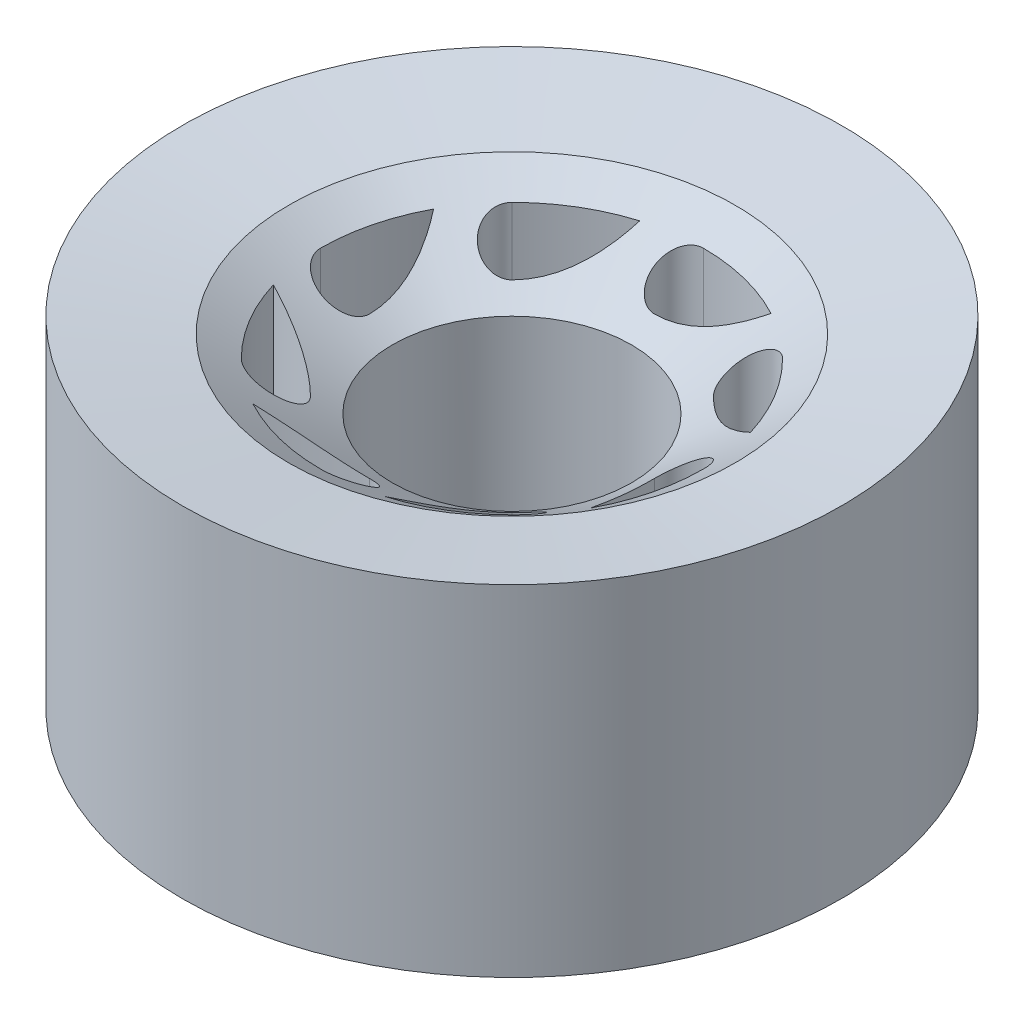
SolidWorks part; units mm, degrees
ref_plane "前视基准面" through (0, 0, 0) normal (0, 0, 1) x (1, 0, 0)
ref_plane "上视基准面" through (0, 0, 0) normal (0, 1, 0) x (1, 0, 0)
ref_plane "右视基准面" through (0, 0, 0) normal (1, 0, 0) x (0, 0, -1)
sketch "草图3" plane through (0, 0, 0) normal (1, 0, 0) x (0, 0, -1)
  line L0 (0, 291.9449) -> (0, 187.2391) construction
  line L1 (0, 211.2391) -> (11.25, 211.2391)
  line L2 (11.25, 211.2391) -> (21, 217.7391)
  line L3 (21, 217.7391) -> (31, 219.2391)
  line L4 (31, 219.2391) -> (31, 187.2391)
  line L5 (0, 187.2391) -> (31, 187.2391)
  line L6 (0, 187.2391) -> (0, 211.2391)
  dimension "D1" = 32
  dimension "D2" = 10
  dimension "D3" = 1.5
  dimension "D4" = 6.5
  dimension "D5" = 11.25
  dimension "D6" = 31
revolve "旋转1" add sketch "草图3" angle 360 about L0
sketch "草图5" plane through (0, 187.2391, 0) normal (0, -1, 0) x (1, 0, 0)
  circle A0 centre (0, 0) radius 4
  dimension "D1" = 8
extrude "切除-拉伸1" cut sketch "草图5" against normal through all contours A0
sketch "草图6" plane through (0, 187.2391, 0) normal (0, -1, 0) x (1, 0, 0)
  line L0 (0, 25.1257) -> (0, -39.6874) construction
  line L1 (-35.1563, 0) -> (34.447, 0) construction
  arc A0 (0, 18) -> (0, 13.4) centre (0, 15.7) cw
  arc A2 (-18, 0) -> (-15.8675, -8.4983) centre (0, 0) ccw
  arc A3 (0, 13.4) -> (-8.4983, 15.8675) centre (0, 29.2683) cw
  arc A4 (0, 18) -> (-8.4983, 15.8675) centre (0, 0) ccw
  arc A5 (12.7279, 12.7279) -> (9.4752, 9.4752) centre (11.1016, 11.1016) cw
  arc A6 (9.4752, 9.4752) -> (5.2108, 17.2293) centre (20.6958, 20.6958) cw
  arc A7 (12.7279, 12.7279) -> (5.2108, 17.2293) centre (0, 0) ccw
  arc A8 (18, 0) -> (13.4, 0) centre (15.7, 0) cw
  arc A9 (13.4, 0) -> (15.8675, 8.4983) centre (29.2683, 0) cw
  arc A10 (18, 0) -> (15.8675, 8.4983) centre (0, 0) ccw
  arc A11 (12.7279, -12.7279) -> (9.4752, -9.4752) centre (11.1016, -11.1016) cw
  arc A12 (9.4752, -9.4752) -> (17.2293, -5.2108) centre (20.6958, -20.6958) cw
  arc A13 (12.7279, -12.7279) -> (17.2293, -5.2108) centre (0, 0) ccw
  arc A14 (0, -18) -> (0, -13.4) centre (0, -15.7) cw
  arc A15 (0, -13.4) -> (8.4983, -15.8675) centre (0, -29.2683) cw
  arc A16 (0, -18) -> (8.4983, -15.8675) centre (0, 0) ccw
  arc A17 (-12.7279, -12.7279) -> (-9.4752, -9.4752) centre (-11.1016, -11.1016) cw
  arc A18 (-9.4752, -9.4752) -> (-5.2108, -17.2293) centre (-20.6958, -20.6958) cw
  arc A19 (-12.7279, -12.7279) -> (-5.2108, -17.2293) centre (0, 0) ccw
  arc A20 (-18, 0) -> (-13.4, 0) centre (-15.7, 0) cw
  arc A21 (-13.4, 0) -> (-15.8675, -8.4983) centre (-29.2683, 0) cw
  arc A22 (-18, 0) -> (-15.8675, -8.4983) centre (0, 0) ccw
  arc A23 (-12.7279, 12.7279) -> (-9.4752, 9.4752) centre (-11.1016, 11.1016) cw
  arc A24 (-9.4752, 9.4752) -> (-17.2293, 5.2108) centre (-20.6958, 20.6958) cw
  arc A25 (-12.7279, 12.7279) -> (-17.2293, 5.2108) centre (0, 0) ccw
  arc A26 (12.7279, -12.7279) -> (17.2293, -5.2108) centre (0, 0) ccw
  arc A27 (0, -18) -> (8.4983, -15.8675) centre (0, 0) ccw
  arc A28 (-12.7279, -12.7279) -> (-5.2108, -17.2293) centre (0, 0) ccw
  point P54 (0, 0)
  dimension "D1" = 2.3
  dimension "D3" = 36
  dimension "D2" = 8.5
  dimension "D5" = 8
extrude "切除-拉伸2" cut sketch "草图6" against normal through all contours A23 A25 A24 | A0 A4 A3 | A5 A7 A6 | A8 A10 A9 | A11 A13 A12 | A14 A16 A15 | A17 A19 A18 | A21 A20 A2
sketch "草图8" plane through (0, 187.2391, 0) normal (0, -1, 0) x (1, 0, 0)
  circle A0 centre (0, 0) radius 11.25
  dimension "D1" = 22.5
extrude "切除-拉伸3" cut sketch "草图8" against normal through all
